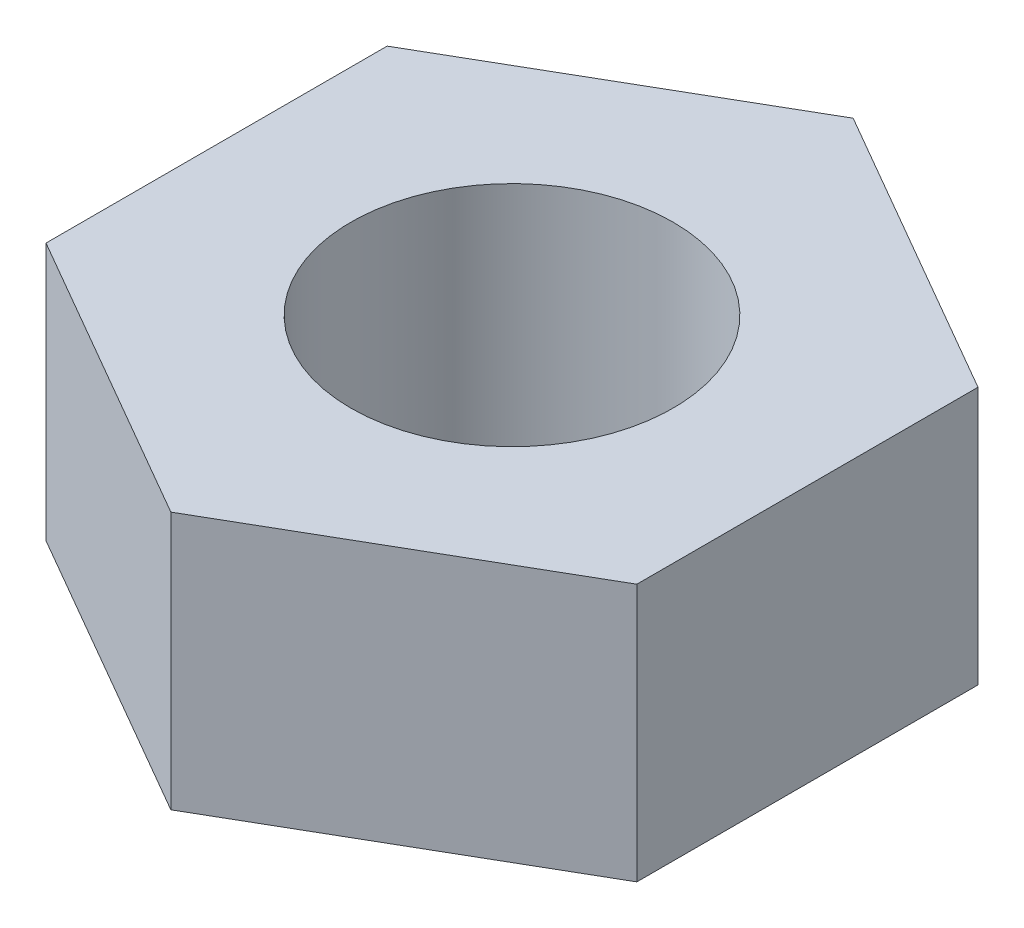
SolidWorks part; units mm, degrees
ref_plane "前视基准面" through (0, 0, 0) normal (0, 0, 1) x (1, 0, 0)
ref_plane "上视基准面" through (0, 0, 0) normal (0, 1, 0) x (1, 0, 0)
ref_plane "右视基准面" through (0, 0, 0) normal (1, 0, 0) x (0, 0, -1)
sketch "草图1" plane through (0, 0, 0) normal (0, 1, 0) x (1, 0, 0)
  line L1 (0, -3.1754) -> (2.75, -1.5877)
  line L2 (2.75, -1.5877) -> (2.75, 1.5877)
  line L3 (2.75, 1.5877) -> (0, 3.1754)
  line L4 (0, 3.1754) -> (-2.75, 1.5877)
  line L5 (-2.75, 1.5877) -> (-2.75, -1.5877)
  line L6 (-2.75, -1.5877) -> (0, -3.1754)
  circle A0 centre (0, 0) radius 2.75 construction
  circle A1 centre (0, 0) radius 1.5
  dimension "D1" = 5.5
extrude "凸台-拉伸1" add sketch "草图1" along normal blind 2.4
